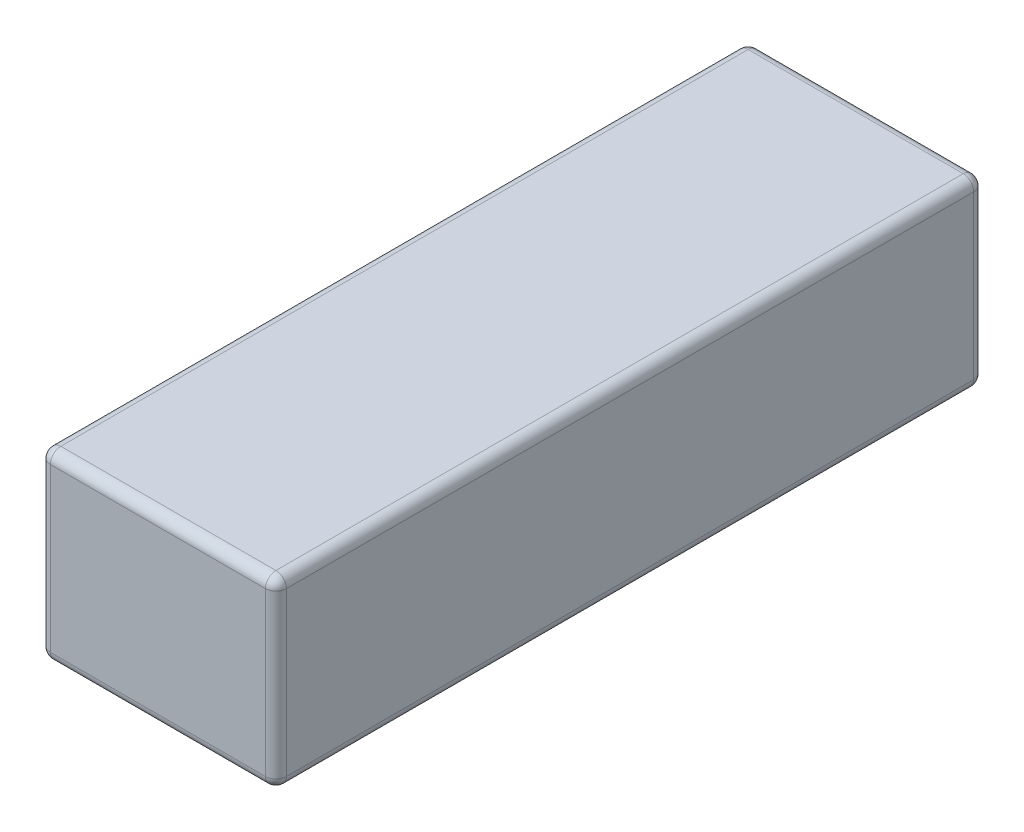
SolidWorks part; units mm, degrees
ref_plane "Front Plane" through (0, 0, 0) normal (0, 0, 1) x (1, 0, 0)
ref_plane "Top Plane" through (0, 0, 0) normal (0, 1, 0) x (1, 0, 0)
ref_plane "Right Plane" through (0, 0, 0) normal (1, 0, 0) x (0, 0, -1)
sketch "Sketch1" plane through (0, 0, 0) normal (0, 0, 1) x (1, 0, 0)
  line L1 (-22.5, 17.5) -> (22.5, 17.5)
  line L2 (-22.5, 17.5) -> (-22.5, -17.5)
  line L3 (-22.5, -17.5) -> (22.5, -17.5)
  line L4 (22.5, 17.5) -> (22.5, -17.5)
  line L5 (-22.5, 17.5) -> (22.5, -17.5) construction
  line L6 (-22.5, -17.5) -> (22.5, 17.5) construction
  point P0 (0, 0)
  dimension "D1" = 35
  dimension "D2" = 45
extrude "Boss-Extrude1" add sketch "Sketch1" along normal mid plane 135
fillet "Fillet1" radius 2 12 edges at (22.5, 0, 67.5) (-22.5, 0, 67.5) (-22.5, 0, -67.5) (22.5, 0, -67.5) (0, -17.5, -67.5) (0, -17.5, 67.5) (-22.5, -17.5, 0) (22.5, -17.5, 0) (0, 17.5, -67.5) (-22.5, 17.5, 0) (22.5, 17.5, 0) (0, 17.5, 67.5)
